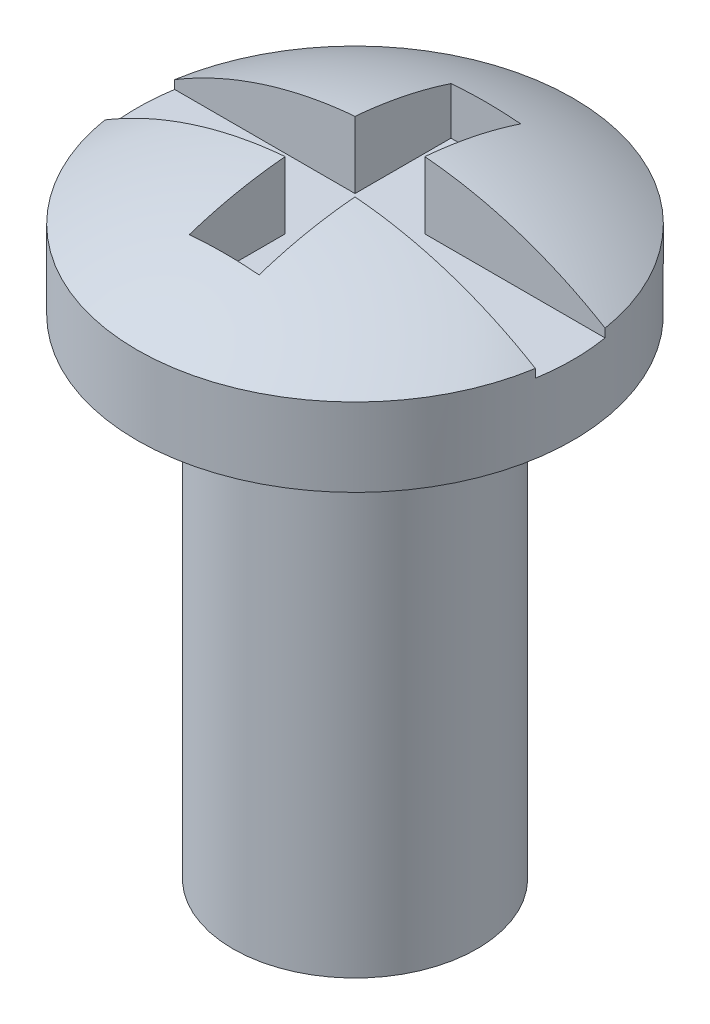
SolidWorks part; units mm, degrees
ref_plane "前视基准面" through (0, 0, 0) normal (0, 0, 1) x (1, 0, 0)
ref_plane "上视基准面" through (0, 0, 0) normal (0, 1, 0) x (1, 0, 0)
ref_plane "右视基准面" through (0, 0, 0) normal (1, 0, 0) x (0, 0, -1)
sketch "草图1" plane through (0, 0, 0) normal (0, 1, 0) x (1, 0, 0)
  circle A0 centre (0, 0) radius 1.75
  dimension "D1" = 3.5
extrude "拉伸1" add sketch "草图1" along normal blind 7
sketch "草图2" plane through (0, 7, 0) normal (0, 1, 0) x (-1, 0, 0)
  circle A0 centre (0, 0) radius 3.125
  dimension "D1" = 6.25
extrude "拉伸2" add sketch "草图2" along normal blind 2
sketch "草图3" plane through (0, 9, 0) normal (0, 1, 0) x (-1, 0, 0)
  line L0 (4.0624, 0) -> (-4.2778, 0) construction
  line L1 (0, -3.5166) -> (0, 3.738) construction
  line L3 (3.5023, -0.5) -> (-3.5023, -0.5)
  line L4 (3.5023, -0.5) -> (3.5023, 0.5)
  line L5 (3.5023, 0.5) -> (-3.5023, 0.5)
  line L6 (-3.5023, -0.5) -> (-3.5023, 0.5)
  dimension "D1" = 1
extrude "切除-拉伸1" cut sketch "草图3" against normal blind 1
sketch "草图4" plane through (0, 9, 0) normal (0, 1, 0) x (-1, 0, 0)
  line L0 (0, -3.8639) -> (0, 3.6765) construction
  line L1 (1.7727, 0) -> (-1.7019, 0) construction
  line L2 (0.5, -1.875) -> (-0.5, -1.875)
  line L3 (0.5, -1.875) -> (0.5, 1.875)
  line L4 (0.5, 1.875) -> (-0.5, 1.875)
  line L5 (-0.5, -1.875) -> (-0.5, 1.875)
  dimension "D1" = 1
  dimension "D2" = 3.75
extrude "切除-拉伸2" cut sketch "草图4" against normal blind 1
sketch "草图5" plane through (0, 0, 0) normal (1, 0, 0) x (0, 0, -1)
  line L0 (0, -2.1059) -> (0, 12.2815) construction
  line L1 (-0.5, 9) -> (-3.125, 9) construction
  line L2 (0, 10.9998) -> (-4.5494, 10.9998)
  line L3 (-4.5494, 6.9119) -> (-4.5494, 10.9998)
  line L5 (0, 10.9998) -> (0, 9)
  arc A2 (0, 9) -> (-4.5494, 6.9119) centre (0, 3) ccw
  dimension "D1" = 6
revolve "切除-旋转16" cut sketch "草图5" angle 360 about L0
